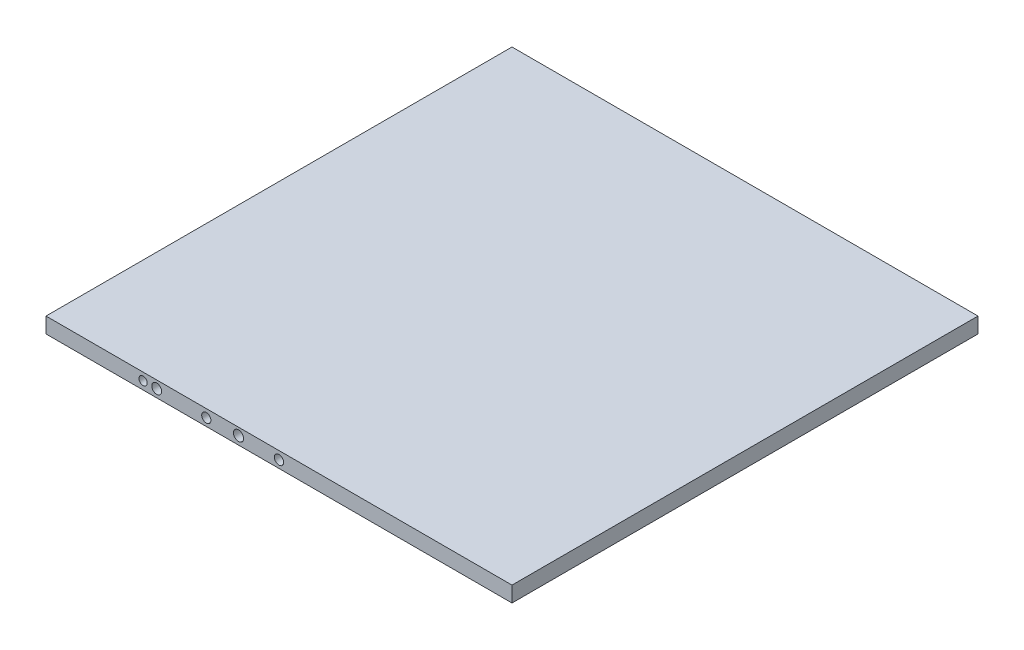
SolidWorks part; units mm, degrees
ref_plane "Front Plane" through (0, 0, 0) normal (0, 0, 1) x (1, 0, 0)
ref_plane "Top Plane" through (0, 0, 0) normal (0, 1, 0) x (1, 0, 0)
ref_plane "Right Plane" through (0, 0, 0) normal (1, 0, 0) x (0, 0, -1)
sketch "Sketch1" plane through (0, 0, 0) normal (0, 1, 0) x (1, 0, 0)
  line L1 (-159.5215, 154.2991) -> (145.2785, 154.2991)
  line L2 (-159.5215, 154.2991) -> (-159.5215, -150.5009)
  line L3 (-159.5215, -150.5009) -> (145.2785, -150.5009)
  line L4 (145.2785, 154.2991) -> (145.2785, -150.5009)
  dimension "D1" = 304.8
  dimension "D2" = 304.8
extrude "Boss-Extrude1" add sketch "Sketch1" along normal blind 10.16
sketch "Sketch2" plane through (0, 0, 0) normal (0, 0, 1) x (1, 0, 0)
  circle A0 centre (-7.1215, 4.9418) radius 3.04
  dimension "D1" = 6.08
extrude "Cut-Extrude1" cut sketch "Sketch2" against normal through all both and the other way through all
sketch "Sketch3" plane through (0, 0, 150.5009) normal (0, 0, 1) x (1, 0, 0)
  circle A0 centre (-54.6795, 4.9418) radius 3
  dimension "D1" = 6
sketch "Sketch4" plane through (0, 0, 150.5009) normal (0, 0, 1) x (1, 0, 0)
  circle A0 centre (-87.1188, 5.2184) radius 3.2281
extrude "Cut-Extrude3" cut sketch "Sketch4" against normal through all
sketch "Sketch5" plane through (0, 0, 150.5009) normal (0, 0, 1) x (1, 0, 0)
  circle A0 centre (-33.5863, 5.3345) radius 3.3081
extrude "Cut-Extrude4" cut sketch "Sketch5" against normal through all both and the other way through all
extrude "Cut-Extrude5" cut sketch "Sketch3" against normal through all both and the other way through all
sketch "Sketch6" plane through (0, 0, 150.5009) normal (0, 0, 1) x (1, 0, 0)
  circle A0 centre (-96.0215, 5.2184) radius 2.7046
  circle A1 centre (-7.1215, 4.9418) radius 3.04 construction
  dimension "D1" = 88.9
extrude "Cut-Extrude6" cut sketch "Sketch6" against normal through all
sketch "Sketch7" plane through (0, 0, 150.5009) normal (0, 0, 1) x (1, 0, 0)
  circle A0 centre (-83.3215, 4.9418) radius 3.175
